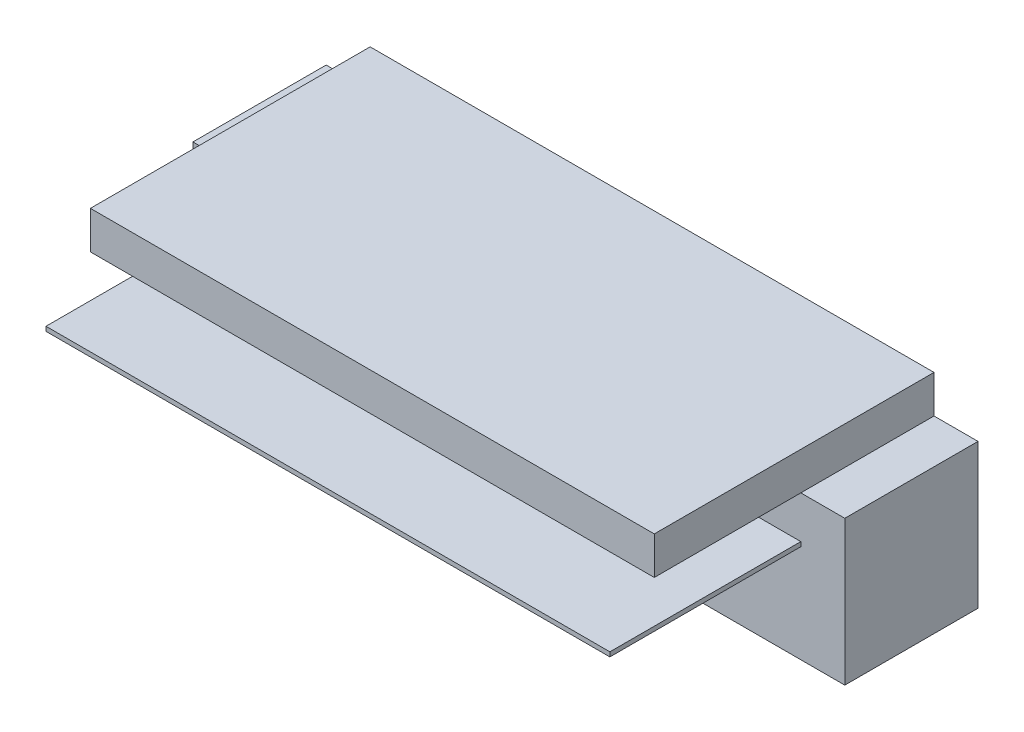
SolidWorks part; units mm, degrees
ref_plane "Front" through (0, 0, 0) normal (0, 0, 1) x (1, 0, 0)
ref_plane "Top" through (0, 0, 0) normal (0, 1, 0) x (1, 0, 0)
ref_plane "Right" through (0, 0, 0) normal (1, 0, 0) x (0, 0, -1)
sketch "Sketch1" plane through (0, 0, 0) normal (0, 1, 0) x (1, 0, 0)
  line L1 (14.6812, -6.3) -> (-14.6812, -6.3)
  line L2 (14.6812, -6.3) -> (14.6812, 6.3)
  line L3 (14.6812, 6.3) -> (-14.6812, 6.3)
  line L4 (-14.6812, -6.3) -> (-14.6812, 6.3)
  line L5 (14.6812, -6.3) -> (-14.6812, 6.3) construction
  line L6 (14.6812, 6.3) -> (-14.6812, -6.3) construction
  point P0 (0, 0)
extrude "Boss-Extrude1" add sketch "Sketch1" along normal blind 8.21
sketch "Sketch4" plane through (0, 0, 6.3) normal (0, 0, 1) x (1, 0, 0)
  line L0 (14.6812, 8.21) -> (14.6812, 0) construction
  line L1 (-14.6812, 0) -> (14.6812, 0)
  line L2 (-14.6812, 0) -> (-14.6812, 6.51)
  line L3 (-14.6812, 6.51) -> (14.6812, 6.51)
  line L4 (14.6812, 0) -> (14.6812, 6.51)
  line L5 (-14.6812, 8.21) -> (14.6812, 8.21) construction
  dimension "D1" = 1.7
extrude "Cut-Extrude2" cut sketch "Sketch4" against normal offset from surface (6.6 mm away) 6 up to face at (0, 4.105, -6.3)
sketch "Sketch2" plane through (0, 0, 6.3) normal (0, 0, 1) x (1, 0, 0)
  line L0 (-14.6812, 8.21) -> (14.6812, 8.21) construction
  line L1 (-12.7, 4.61) -> (12.7, 4.61)
  line L2 (-12.7, 4.61) -> (-12.7, 4.41)
  line L3 (-12.7, 4.41) -> (12.7, 4.41)
  line L4 (12.7, 4.61) -> (12.7, 4.41)
  point P4 (-12.7, 4.51)
  point P7 (0, 8.21)
  point P8 (0, 4.61)
  dimension "D1" = 3.7
  dimension "D2" = 0.2
  dimension "D4" = 25.4
extrude "Boss-Extrude2" add sketch "Sketch2" along normal offset from surface (14.6 mm away) 2 from surface at -12.6 up to face at (0, 7.36, 6.3) offset beyond the face yes starting at face at (0, 4.105, -6.3)
sketch "Sketch3" plane through (0, 8.21, 0) normal (0, 1, 0) x (1, 0, 0)
  line L0 (14.6812, 6.3) -> (-14.6812, 6.3) construction
  line L1 (-14.6812, -6.3) -> (-12.7, -6.3)
  line L2 (-14.6812, -6.3) -> (-14.6812, 6.3)
  line L3 (-14.6812, 6.3) -> (-12.7, 6.3)
  line L4 (-12.7, -6.3) -> (-12.7, 6.3)
  line L5 (-14.6812, -6.3) -> (14.6812, -6.3) construction
  line L6 (14.6812, 6.3) -> (12.7, 6.3)
  line L7 (14.6812, 6.3) -> (14.6812, -6.3)
  line L8 (14.6812, -6.3) -> (12.7, -6.3)
  line L9 (12.7, 6.3) -> (12.7, -6.3)
  line L10 (-12.7, -8.3) -> (-12.7, 0.3) construction
extrude "Cut-Extrude1" cut sketch "Sketch3" against normal blind 1.7
